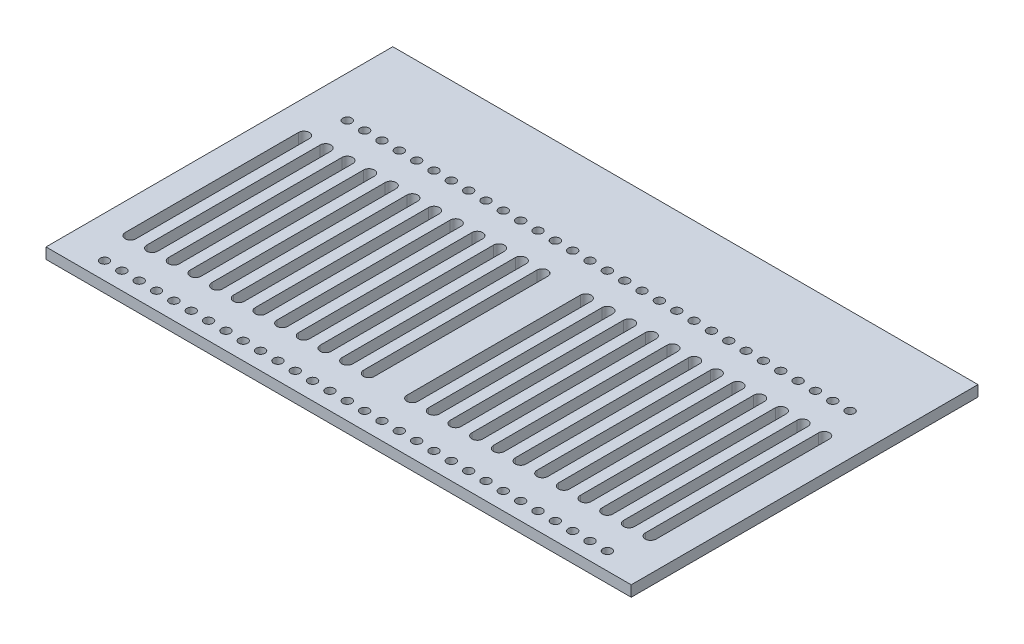
SolidWorks part; units mm, degrees
ref_plane "前视基准面" through (0, 0, 0) normal (0, 0, 1) x (1, 0, 0)
ref_plane "上视基准面" through (0, 0, 0) normal (0, 1, 0) x (1, 0, 0)
ref_plane "右视基准面" through (0, 0, 0) normal (1, 0, 0) x (0, 0, -1)
sketch "Sketch1" plane through (0, 0, 0) normal (0, 1, 0) x (1, 0, 0)
  line L0 (0, 0) -> (270, 0)
  line L1 (270, 0) -> (270, -160)
  line L2 (270, -160) -> (0, -160)
  line L3 (0, -160) -> (0, 0)
  dimension "D1" = 270
  dimension "D2" = 160
extrude "Boss-Extrude1" add sketch "Sketch1" along normal blind 5
sketch "Sketch2" plane through (0, 5, 0) normal (0, 1, 0) x (1, 0, 0)
  line L0 (135, 0) -> (135, -178.1193) construction
  line L1 (270, 0) -> (0, 0) construction
  line L2 (-16.4594, -152) -> (295.4905, -152) construction
  line L3 (0, -160) -> (270, -160) construction
  line L4 (139, 0) -> (139, -178.1193) construction
  line L5 (-16.4594, -96) -> (295.4905, -96) construction
  circle A0 centre (139, -152) radius 2.025
  circle A1 centre (147, -152) radius 2.025
  circle A2 centre (155, -152) radius 2.025
  circle A3 centre (163, -152) radius 2.025
  circle A4 centre (171, -152) radius 2.025
  circle A5 centre (179, -152) radius 2.025
  circle A6 centre (187, -152) radius 2.025
  circle A7 centre (195, -152) radius 2.025
  circle A8 centre (203, -152) radius 2.025
  circle A9 centre (211, -152) radius 2.025
  circle A10 centre (219, -152) radius 2.025
  circle A11 centre (227, -152) radius 2.025
  circle A12 centre (235, -152) radius 2.025
  circle A13 centre (243, -152) radius 2.025
  circle A14 centre (251, -152) radius 2.025
  circle A15 centre (19, -152) radius 2.025
  circle A16 centre (27, -152) radius 2.025
  circle A17 centre (35, -152) radius 2.025
  circle A18 centre (43, -152) radius 2.025
  circle A19 centre (51, -152) radius 2.025
  circle A20 centre (59, -152) radius 2.025
  circle A21 centre (67, -152) radius 2.025
  circle A22 centre (75, -152) radius 2.025
  circle A23 centre (83, -152) radius 2.025
  circle A24 centre (91, -152) radius 2.025
  circle A25 centre (99, -152) radius 2.025
  circle A26 centre (107, -152) radius 2.025
  circle A27 centre (115, -152) radius 2.025
  circle A28 centre (123, -152) radius 2.025
  circle A29 centre (131, -152) radius 2.025
  circle A30 centre (131, -40) radius 2.025
  circle A31 centre (123, -40) radius 2.025
  circle A32 centre (115, -40) radius 2.025
  circle A33 centre (107, -40) radius 2.025
  circle A34 centre (99, -40) radius 2.025
  circle A35 centre (91, -40) radius 2.025
  circle A36 centre (83, -40) radius 2.025
  circle A37 centre (75, -40) radius 2.025
  circle A38 centre (67, -40) radius 2.025
  circle A39 centre (59, -40) radius 2.025
  circle A40 centre (51, -40) radius 2.025
  circle A41 centre (43, -40) radius 2.025
  circle A42 centre (35, -40) radius 2.025
  circle A43 centre (27, -40) radius 2.025
  circle A44 centre (19, -40) radius 2.025
  circle A45 centre (251, -40) radius 2.025
  circle A46 centre (243, -40) radius 2.025
  circle A47 centre (235, -40) radius 2.025
  circle A48 centre (227, -40) radius 2.025
  circle A49 centre (219, -40) radius 2.025
  circle A50 centre (211, -40) radius 2.025
  circle A51 centre (203, -40) radius 2.025
  circle A52 centre (195, -40) radius 2.025
  circle A53 centre (187, -40) radius 2.025
  circle A54 centre (179, -40) radius 2.025
  circle A55 centre (171, -40) radius 2.025
  circle A56 centre (163, -40) radius 2.025
  circle A57 centre (155, -40) radius 2.025
  circle A58 centre (147, -40) radius 2.025
  circle A59 centre (139, -40) radius 2.025
  dimension "D3" = 4.05
  dimension "D1" = 8
  dimension "D5" = 112
  dimension "D2" = 4
  dimension "D6" = 56
  dimension "D4" = 15
extrude "Cut-Extrude1" cut sketch "Sketch2" against normal through all
sketch "Sketch3" plane through (0, 5, 0) normal (0, 1, 0) x (1, 0, 0)
  line L0 (135, 0) -> (135, -119.0408) construction
  line L1 (270, 0) -> (0, 0) construction
  line L2 (145, -56) -> (145, -136) construction
  line L3 (147.5, -56) -> (147.5, -136)
  line L4 (142.5, -56) -> (142.5, -136)
  line L5 (155, -56) -> (155, -136) construction
  line L6 (157.5, -56) -> (157.5, -136)
  line L7 (152.5, -56) -> (152.5, -136)
  line L8 (165, -56) -> (165, -136) construction
  line L9 (167.5, -56) -> (167.5, -136)
  line L10 (162.5, -56) -> (162.5, -136)
  line L11 (175, -56) -> (175, -136) construction
  line L12 (177.5, -56) -> (177.5, -136)
  line L13 (172.5, -56) -> (172.5, -136)
  line L14 (185, -56) -> (185, -136) construction
  line L15 (187.5, -56) -> (187.5, -136)
  line L16 (182.5, -56) -> (182.5, -136)
  line L17 (195, -56) -> (195, -136) construction
  line L18 (197.5, -56) -> (197.5, -136)
  line L19 (192.5, -56) -> (192.5, -136)
  line L20 (205, -56) -> (205, -136) construction
  line L21 (207.5, -56) -> (207.5, -136)
  line L22 (202.5, -56) -> (202.5, -136)
  line L23 (215, -56) -> (215, -136) construction
  line L24 (217.5, -56) -> (217.5, -136)
  line L25 (212.5, -56) -> (212.5, -136)
  line L26 (225, -56) -> (225, -136) construction
  line L27 (227.5, -56) -> (227.5, -136)
  line L28 (222.5, -56) -> (222.5, -136)
  line L29 (235, -56) -> (235, -136) construction
  line L30 (237.5, -56) -> (237.5, -136)
  line L31 (232.5, -56) -> (232.5, -136)
  line L32 (245, -56) -> (245, -136) construction
  line L33 (247.5, -56) -> (247.5, -136)
  line L34 (242.5, -56) -> (242.5, -136)
  line L35 (255, -56) -> (255, -136) construction
  line L36 (257.5, -56) -> (257.5, -136)
  line L37 (252.5, -56) -> (252.5, -136)
  line L38 (125, -56) -> (125, -136) construction
  line L39 (122.5, -56) -> (122.5, -136)
  line L40 (127.5, -56) -> (127.5, -136)
  line L41 (115, -56) -> (115, -136) construction
  line L42 (112.5, -56) -> (112.5, -136)
  line L43 (117.5, -56) -> (117.5, -136)
  line L44 (105, -56) -> (105, -136) construction
  line L45 (102.5, -56) -> (102.5, -136)
  line L46 (107.5, -56) -> (107.5, -136)
  line L47 (95, -56) -> (95, -136) construction
  line L48 (92.5, -56) -> (92.5, -136)
  line L49 (97.5, -56) -> (97.5, -136)
  line L50 (85, -56) -> (85, -136) construction
  line L51 (82.5, -56) -> (82.5, -136)
  line L52 (87.5, -56) -> (87.5, -136)
  line L53 (75, -56) -> (75, -136) construction
  line L54 (72.5, -56) -> (72.5, -136)
  line L55 (77.5, -56) -> (77.5, -136)
  line L56 (65, -56) -> (65, -136) construction
  line L57 (62.5, -56) -> (62.5, -136)
  line L58 (67.5, -56) -> (67.5, -136)
  line L59 (55, -56) -> (55, -136) construction
  line L60 (52.5, -56) -> (52.5, -136)
  line L61 (57.5, -56) -> (57.5, -136)
  line L62 (45, -56) -> (45, -136) construction
  line L63 (42.5, -56) -> (42.5, -136)
  line L64 (47.5, -56) -> (47.5, -136)
  line L65 (35, -56) -> (35, -136) construction
  line L66 (32.5, -56) -> (32.5, -136)
  line L67 (37.5, -56) -> (37.5, -136)
  line L68 (25, -56) -> (25, -136) construction
  line L69 (22.5, -56) -> (22.5, -136)
  line L70 (27.5, -56) -> (27.5, -136)
  line L71 (15, -56) -> (15, -136) construction
  line L72 (12.5, -56) -> (12.5, -136)
  line L73 (17.5, -56) -> (17.5, -136)
  arc A0 (147.5, -56) -> (142.5, -56) centre (145, -56) ccw
  arc A1 (142.5, -136) -> (147.5, -136) centre (145, -136) ccw
  arc A2 (157.5, -56) -> (152.5, -56) centre (155, -56) ccw
  arc A3 (152.5, -136) -> (157.5, -136) centre (155, -136) ccw
  arc A4 (167.5, -56) -> (162.5, -56) centre (165, -56) ccw
  arc A5 (162.5, -136) -> (167.5, -136) centre (165, -136) ccw
  arc A6 (177.5, -56) -> (172.5, -56) centre (175, -56) ccw
  arc A7 (172.5, -136) -> (177.5, -136) centre (175, -136) ccw
  arc A8 (187.5, -56) -> (182.5, -56) centre (185, -56) ccw
  arc A9 (182.5, -136) -> (187.5, -136) centre (185, -136) ccw
  arc A10 (197.5, -56) -> (192.5, -56) centre (195, -56) ccw
  arc A11 (192.5, -136) -> (197.5, -136) centre (195, -136) ccw
  arc A12 (207.5, -56) -> (202.5, -56) centre (205, -56) ccw
  arc A13 (202.5, -136) -> (207.5, -136) centre (205, -136) ccw
  arc A14 (217.5, -56) -> (212.5, -56) centre (215, -56) ccw
  arc A15 (212.5, -136) -> (217.5, -136) centre (215, -136) ccw
  arc A16 (227.5, -56) -> (222.5, -56) centre (225, -56) ccw
  arc A17 (222.5, -136) -> (227.5, -136) centre (225, -136) ccw
  arc A18 (237.5, -56) -> (232.5, -56) centre (235, -56) ccw
  arc A19 (232.5, -136) -> (237.5, -136) centre (235, -136) ccw
  arc A20 (247.5, -56) -> (242.5, -56) centre (245, -56) ccw
  arc A21 (242.5, -136) -> (247.5, -136) centre (245, -136) ccw
  arc A22 (257.5, -56) -> (252.5, -56) centre (255, -56) ccw
  arc A23 (252.5, -136) -> (257.5, -136) centre (255, -136) ccw
  arc A24 (122.5, -56) -> (127.5, -56) centre (125, -56) cw
  arc A25 (127.5, -136) -> (122.5, -136) centre (125, -136) cw
  arc A26 (112.5, -56) -> (117.5, -56) centre (115, -56) cw
  arc A27 (117.5, -136) -> (112.5, -136) centre (115, -136) cw
  arc A28 (102.5, -56) -> (107.5, -56) centre (105, -56) cw
  arc A29 (107.5, -136) -> (102.5, -136) centre (105, -136) cw
  arc A30 (92.5, -56) -> (97.5, -56) centre (95, -56) cw
  arc A31 (97.5, -136) -> (92.5, -136) centre (95, -136) cw
  arc A32 (82.5, -56) -> (87.5, -56) centre (85, -56) cw
  arc A33 (87.5, -136) -> (82.5, -136) centre (85, -136) cw
  arc A34 (72.5, -56) -> (77.5, -56) centre (75, -56) cw
  arc A35 (77.5, -136) -> (72.5, -136) centre (75, -136) cw
  arc A36 (62.5, -56) -> (67.5, -56) centre (65, -56) cw
  arc A37 (67.5, -136) -> (62.5, -136) centre (65, -136) cw
  arc A38 (52.5, -56) -> (57.5, -56) centre (55, -56) cw
  arc A39 (57.5, -136) -> (52.5, -136) centre (55, -136) cw
  arc A40 (42.5, -56) -> (47.5, -56) centre (45, -56) cw
  arc A41 (47.5, -136) -> (42.5, -136) centre (45, -136) cw
  arc A42 (32.5, -56) -> (37.5, -56) centre (35, -56) cw
  arc A43 (37.5, -136) -> (32.5, -136) centre (35, -136) cw
  arc A44 (22.5, -56) -> (27.5, -56) centre (25, -56) cw
  arc A45 (27.5, -136) -> (22.5, -136) centre (25, -136) cw
  arc A46 (12.5, -56) -> (17.5, -56) centre (15, -56) cw
  arc A47 (17.5, -136) -> (12.5, -136) centre (15, -136) cw
  point P6 (145, -96)
  point P14 (155, -96)
  point P21 (165, -96)
  point P28 (175, -96)
  point P35 (185, -96)
  point P42 (195, -96)
  point P49 (205, -96)
  point P56 (215, -96)
  point P63 (225, -96)
  point P70 (235, -96)
  point P77 (245, -96)
  point P84 (255, -96)
  point P90 (125, -96)
  point P97 (115, -96)
  point P104 (105, -96)
  point P111 (95, -96)
  point P118 (85, -96)
  point P125 (75, -96)
  point P132 (65, -96)
  point P139 (55, -96)
  point P146 (45, -96)
  point P153 (35, -96)
  point P160 (25, -96)
  point P167 (15, -96)
  dimension "D3" = 2.5
  dimension "D1" = 56
  dimension "D2" = 80
  dimension "D4" = 10
  dimension "D6" = 110
  dimension "D5" = 12
extrude "Cut-Extrude2" cut sketch "Sketch3" against normal through all
